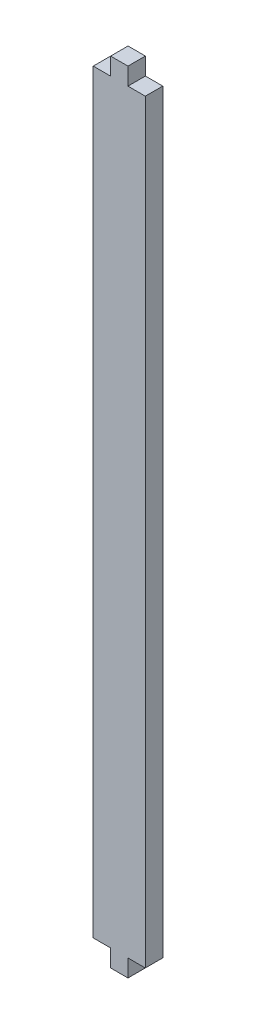
SolidWorks part; units mm, degrees
ref_plane "Front Plane" through (0, 0, 0) normal (0, 0, 1) x (1, 0, 0)
ref_plane "Top Plane" through (0, 0, 0) normal (0, 1, 0) x (1, 0, 0)
ref_plane "Right Plane" through (0, 0, 0) normal (1, 0, 0) x (0, 0, -1)
sketch "Sketch1" plane through (0, 0, 0) normal (0, 0, 1) x (1, 0, 0)
  line L1 (0, 0) -> (14.4, 0)
  line L2 (0, 0) -> (0, 218.44)
  line L3 (0, 218.44) -> (14.4, 218.44)
  line L4 (14.4, 0) -> (14.4, 218.44)
  line L5 (0, 0) -> (14.4, 218.44) construction
  line L6 (0, 218.44) -> (14.4, 0) construction
  point P4 (7.2, 109.22)
  dimension "D1" = 218.44
  dimension "D2" = 14.4
extrude "Boss-Extrude1" add sketch "Sketch1" along normal blind 4.826
ref_point "Point1"
sketch "Sketch2" plane through (0, 0, 4.826) normal (0, 0, 1) x (1, 0, 0)
  line L0 (4.8, 0) -> (9.6, 0) construction
  line L1 (0, 0) -> (4.8, 0)
  line L2 (0, 0) -> (0, 4.8)
  line L3 (0, 4.8) -> (4.8, 4.8)
  line L4 (4.8, 0) -> (4.8, 4.8)
  line L5 (14.4, 0) -> (9.6, 0)
  line L6 (14.4, 0) -> (14.4, 4.8)
  line L7 (14.4, 4.8) -> (9.6, 4.8)
  line L8 (9.6, 0) -> (9.6, 4.8)
  line L9 (14.4, 218.44) -> (0, 218.44) construction
  line L10 (0, 218.44) -> (4.8, 218.44)
  line L11 (0, 218.44) -> (0, 213.64)
  line L12 (0, 213.64) -> (4.8, 213.64)
  line L13 (4.8, 218.44) -> (4.8, 213.64)
  line L14 (0, 218.44) -> (0, 0) construction
  line L15 (4.8, 218.44) -> (9.6, 218.44) construction
  line L16 (14.4, 218.44) -> (9.6, 218.44)
  line L17 (14.4, 218.44) -> (14.4, 213.64)
  line L18 (14.4, 213.64) -> (9.6, 213.64)
  line L19 (9.6, 218.44) -> (9.6, 213.64)
  line L20 (4.8, 218.44) -> (9.6, 218.44) construction
  dimension "D1" = 4.8
  dimension "D2" = 4.8
extrude "Cut-Extrude1" cut sketch "Sketch2" against normal through all
equation "\"MDF\"= 4.8mm"
equation "\"Foamcore\"= 4.6mm"
equation "\"GMaterial\"= \"MDF\""
equation "\"PCB\" = 1.6mm"
equation "\"BaseWidth\" = 10in"
equation "\"SkidLength\" = 1in"
equation "\"SkidClearance\" = 0.4in"
equation "\"MotorMountLength\" = 2in"
equation "\"MotorMountWidth\" = \"GMaterial\""
equation "\"MotorMountHeight\" = 2.25in"
equation "\"UnoStackWidth\" = 77.4mm"
equation "\"UnoStackLength\" = 79.8mm"
equation "\"UnoStackHeight\" = 34.2mm"
equation "\"TallHexRiserHeight\" = 22.2mm"
equation "\"PingPongBallSize\" = 40mm"
equation "\"BarrelLength\" = 9in"
equation "\"BarrelSize\" = \"PingPongBallSize\""
equation "\"PlatformLength\" = 4in"
equation "\"PlatformWidth\" = 6in"
equation "\"WheelDiameter\"=2.99213"
equation "\"ServoMountHeight\"=2.49223"
equation "\"ServoGearHeight\" = 0.95330261in"
equation "\"ServoMountLength\"= 1.53774"
equation "\"PivotHoleRadius\"= 0.616358"
equation "\"PlatformMountHeight\" = 3.19"
equation "\"TensionOffSet\"= .3mm"
equation "\"MotorMountWedge\"=0.333333"
equation "\"LaserCutterOffset\"= .3mm"
equation "\"BumperWidth\"=11"
equation "\"PitcherWheelCompression\" = 2.5mm"
equation "\"PitchingWheelWidth\" = 26.2mm"
equation "\"PitchingWheelDiameter\" = 65.5mm"
equation "\"PitchingWheelMountOffset\" = 8.4mm"
equation "\"PitchingWheelInnerDiameter\" = 45.5mm"
equation "\"PitchingWheelBoltShoulder\" = 4.5mm"
equation "\"BrassCouplingLength\" = 18mm"
equation "\"PitchingMotorHeight\" = 57.0mm"
equation "\"PitchingMotorShaftTopHeight\" = \"PitchingMotorHeight\" - 44.1mm"
equation "\"PitchingMotorBodyHeight\" = 38mm"
equation "\"PitchingMotorTopShoulderHeight\" = 40.6mm - \"PitchingMotorBodyHeight\" "
equation "\"PitchingMotorBottomShoulderHeight\" = 40.2mm - \"PitchingMotorBodyHeight\""
equation "\"PitchingMotorBottomShaftHeight\" = \"PitchingMotorHeight\" - \"PitchingMotorShaftTopHeight\" - \"PitchingMotorTopShoulderHeight\" - \"PitchingMotorBodyHeight\" - \"PitchingMotorBottomShoulderHeight\""
equation "\"PitchingMotorShaftDiameter\" = 2.2mm"
equation "\"PitchingMotorBodyDiameter\" = 27.4mm"
equation "\"PitchingMotorTopShoulderDiameter\" = 9.8mm"
equation "\"PitchingMotorBottomShoulderDiameter\" = 9.8mm"
equation "\"BrassCouplingHexSize\" = 12mm"
equation "\"BrassCouplingBoreSize\" = 3.17mm"
equation "\"PitchingMotorMountingHoleDistance\" = 16mm"
equation "\"Acrylic\" = 4.4mm"
equation "\"PitchingMotorDistance\" = \"PitchingWheelDiameter\" + \"PingPongBallSize\" - \"PitcherWheelCompression\"*2"
equation "\"PitchingMotorPlatformOffset\"=1"
equation "\"ServoPlatformOffset\"=1.64173"
equation "\"BallBearingDiameter\" = 22mm"
equation "\"BallBearingWidth\" = 9mm"
equation "\"BallBearingHexShoulder\" = 9mm - 5.9mm"
equation "\"BallBearingHexSize\" = .36in"
equation "\"PlatformMountFootLength\"=0.857143"
equation "\"WheelWidth\"= 26mm"
equation "\"ServoMountReductionBackHeight\"=2.25"
equation "\"PlatformBottomWidthThird\" =  0.857143in"
equation "\"PlatformMountBackReductionHeight\"= 2.5in"
equation "\"PlatformMountBackReductionWidth\"= 3/7in"
equation "\"PlatformMountFrontReductionWidth\" =  1.46226in"
equation "\"PlatformMountFrontReductionHeight\" = 2.5in"
equation "\"D2@Sketch1\"=\"MDF\"*3"
equation "\"D1@Sketch2\"=\"MDF\""
equation "\"D2@Sketch2\"=\"MDF\""
